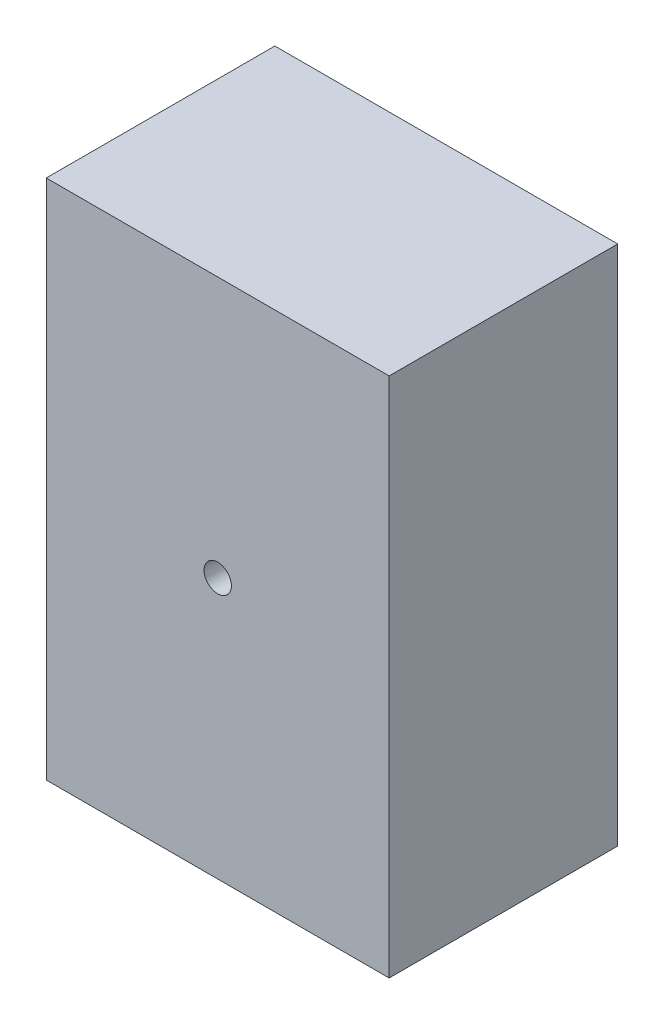
SolidWorks part; units mm, degrees
ref_plane "Front Plane" through (0, 0, 0) normal (0, 0, 1) x (1, 0, 0)
ref_plane "Top Plane" through (0, 0, 0) normal (0, 1, 0) x (1, 0, 0)
ref_plane "Right Plane" through (0, 0, 0) normal (1, 0, 0) x (0, 0, -1)
sketch "Sketch2" plane through (0, 0, 0) normal (0, 0, 1) x (1, 0, 0)
  line L1 (19.05, -28.9719) -> (-19.05, -28.9719)
  line L2 (19.05, -28.9719) -> (19.05, 28.9719)
  line L3 (19.05, 28.9719) -> (-19.05, 28.9719)
  line L4 (-19.05, -28.9719) -> (-19.05, 28.9719)
  line L5 (19.05, -28.9719) -> (-19.05, 28.9719) construction
  line L6 (19.05, 28.9719) -> (-19.05, -28.9719) construction
  point P0 (0, 0)
  dimension "D1" = 38.1
  dimension "D2" = 57.9437
extrude "Boss-Extrude1" add sketch "Sketch2" along normal blind 25.4
ref_plane "Plane1" through (0, 0, 25.4) normal (0, 0, 1) x (1, 0, 0)
sketch "Sketch3" plane through (0, 0, 25.4) normal (0, 0, 1) x (1, 0, 0)
  circle A0 centre (0, 0) radius 1.52
  point P2 (0, 0)
extrude "Cut-Extrude1" cut sketch "Sketch3" against normal through all
